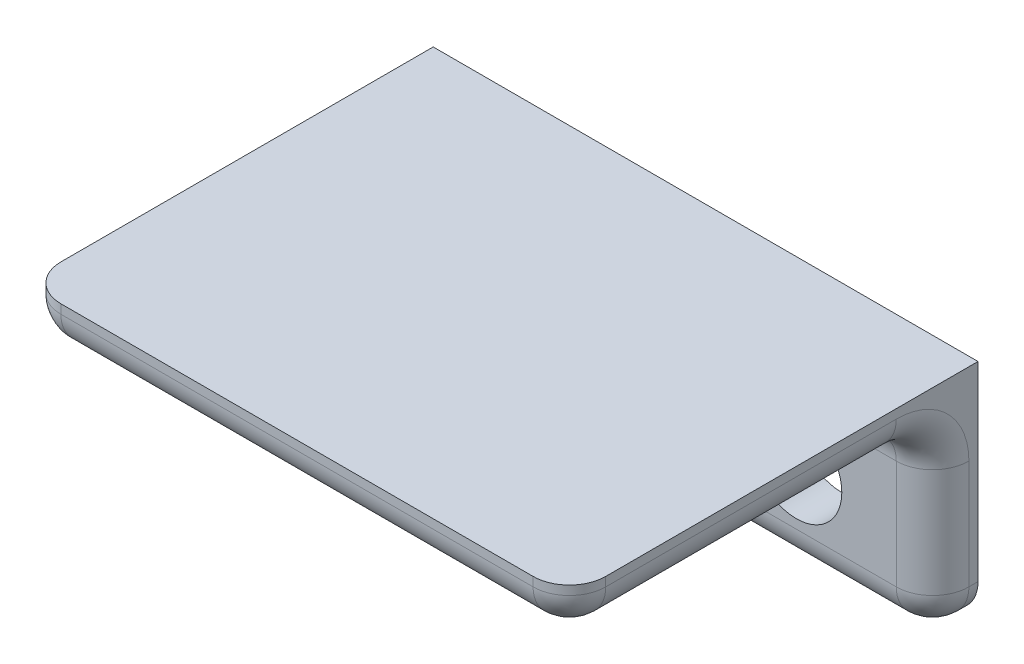
SolidWorks part; units mm, degrees
ref_plane "Front" through (0, 0, 0) normal (0, 0, 1) x (1, 0, 0)
ref_plane "Top" through (0, 0, 0) normal (0, 1, 0) x (1, 0, 0)
ref_plane "Right" through (0, 0, 0) normal (1, 0, 0) x (0, 0, -1)
sketch "Sketch1" plane through (0, 0, 0) normal (0, 0, 1) x (-1, 0, 0)
  line L1 (-56.639, 41.1) -> (-26.639, 41.1)
  line L2 (-56.639, 41.1) -> (-56.639, 51.1)
  line L3 (-56.639, 51.1) -> (-26.639, 51.1)
  line L4 (-26.639, 41.1) -> (-26.639, 51.1)
  line L6 (-56.639, 46.1) -> (-41.639, 46.1) construction
  line L7 (-41.639, 51.1) -> (-41.639, 41.1) construction
  circle A0 centre (-49.139, 46.1) radius 2.5
  circle A1 centre (-34.139, 46.1) radius 2.5
  dimension "D3" = 5
  dimension "D2" = 30
extrude "Boss-Extrude1" add sketch "Sketch1" along normal blind 2.5 contours A1
sketch "Sketch2" plane through (0, 0, 0) normal (0, 0, -1) x (-1, 0, 0)
  line L0 (-56.639, -51.1) -> (-56.639, -41.1) construction
  line L1 (-26.639, -41.1) -> (-56.639, -41.1)
  line L2 (-26.639, -41.1) -> (-26.639, -38.6)
  line L3 (-26.639, -38.6) -> (-56.639, -38.6)
  line L4 (-56.639, -41.1) -> (-56.639, -38.6)
  dimension "D1" = 2.5
extrude "Boss-Extrude2" add sketch "Sketch2" against normal blind 22.5
fillet "Fillet1" radius 2 11 edges at (26.639, -51.1, 1.25) (41.639, -51.1, 2.5) (56.639, -51.1, 1.25) (26.639, -41.1, 12.5) (56.639, -41.1, 12.5) (26.639, -46.1, 2.5) (56.639, -46.1, 2.5) (41.639, -41.1, 22.5) (56.639, -39.85, 22.5) (26.639, -39.85, 22.5) (41.639, -41.1, 2.5)
